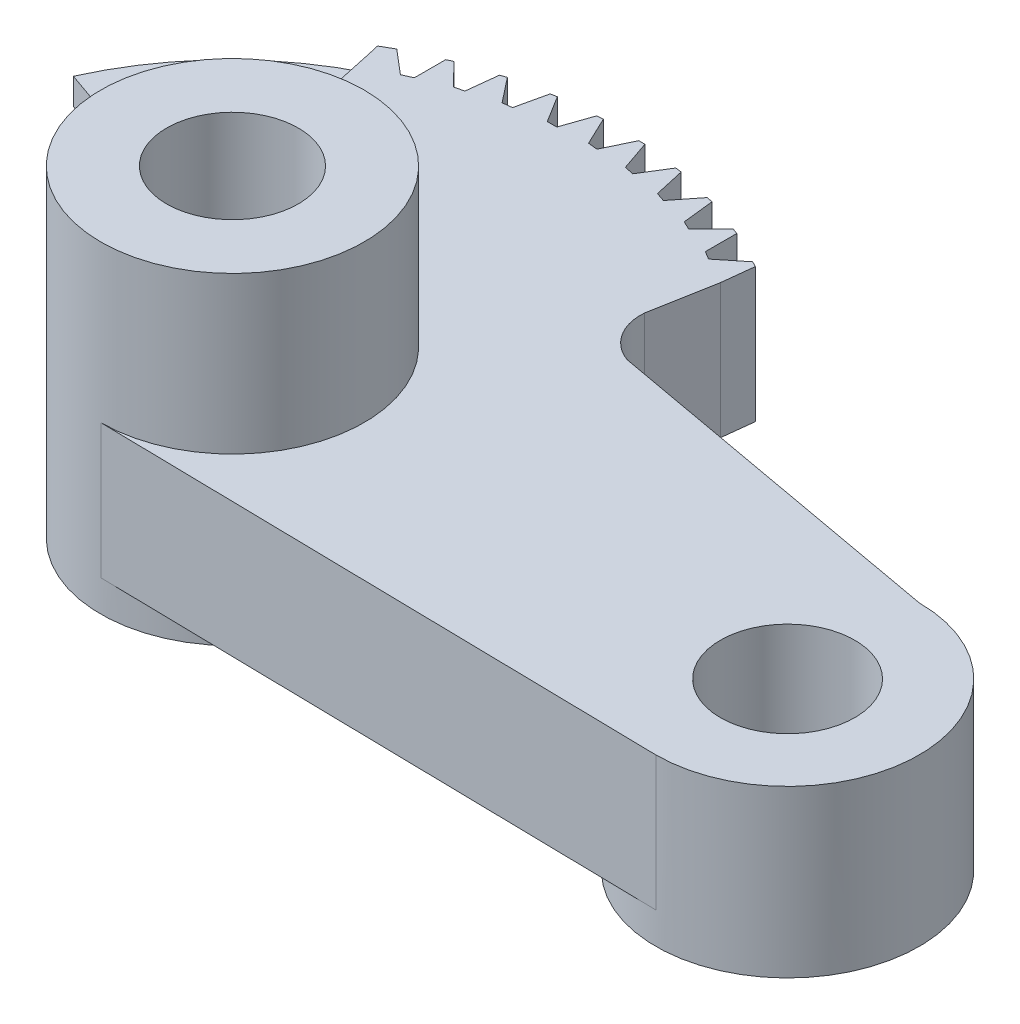
SolidWorks part; units mm, degrees
ref_plane "Спереди" through (0, 0, 0) normal (0, 0, 1) x (1, 0, 0)
ref_plane "Сверху" through (0, 0, 0) normal (0, 1, 0) x (1, 0, 0)
ref_plane "Справа" through (0, 0, 0) normal (1, 0, 0) x (0, 0, -1)
sketch "Эскиз1" plane through (0, 0, 0) normal (0, 1, 0) x (1, 0, 0)
  line L0 (-8.1147, 3.9642) -> (30.3411, -3.1046) construction
  line L1 (-7.0258, 12.1759) -> (-7.131, 12.6394)
  line L2 (0, -5) -> (21.4669, -5.3883)
  line L3 (21.4669, 4.6117) -> (7.9243, 7.0621)
  line L4 (6.718, 8.9283) -> (7.1612, 11.3779)
  line L5 (-2.8983, 13.1359) -> (-3.6342, 14.0716)
  line L6 (-4.339, 12.734) -> (-5.1742, 13.5822)
  line L7 (-3.9893, 12.8157) -> (-3.8571, 13.9987)
  line L9 (-7.131, 12.6394) -> (-6.6667, 12.9059)
  line L10 (-6.6667, 12.9059) -> (-5.7516, 12.1288)
  line L11 (-5.7516, 12.1288) -> (-5.3876, 12.2946)
  line L12 (-3.8571, 13.9987) -> (-3.6342, 14.0716)
  line L13 (-1.422, 13.3754) -> (-2.0494, 14.387)
  line L14 (-2.5417, 13.1782) -> (-2.279, 14.3393)
  line L39 (-2.279, 14.3393) -> (-2.0494, 14.387)
  line L40 (0.0718, 13.4494) -> (-0.4394, 14.5244)
  line L41 (-1.0629, 13.3778) -> (-0.6729, 14.5025)
  line L42 (-0.6729, 14.5025) -> (-0.4394, 14.5244)
  line L43 (1.5646, 13.3571) -> (1.1759, 14.4822)
  line L44 (0.4289, 13.412) -> (0.9414, 14.4864)
  line L45 (0.9414, 14.4864) -> (1.1759, 14.4822)
  line L46 (3.0379, 13.0996) -> (2.7766, 14.261)
  line L47 (1.9154, 13.2803) -> (2.544, 14.2911)
  line L48 (2.544, 14.2911) -> (2.7766, 14.261)
  line L49 (4.4735, 12.6801) -> (4.3427, 13.8633)
  line L50 (3.378, 12.9843) -> (4.1149, 13.9191)
  line L51 (4.1149, 13.9191) -> (4.3427, 13.8633)
  line L52 (5.8536, 12.1038) -> (5.8551, 13.2942)
  line L53 (4.7987, 12.5278) -> (5.6349, 13.375)
  line L54 (5.6349, 13.375) -> (5.8551, 13.2942)
  line L55 (7.1612, 11.3779) -> (7.2948, 12.5607)
  line L56 (6.1599, 11.9163) -> (7.085, 12.6654)
  line L57 (7.085, 12.6654) -> (7.2948, 12.5607)
  line L58 (-4.339, 12.734) -> (-3.9893, 12.8157)
  line L59 (-2.8983, 13.1359) -> (-2.5417, 13.1782)
  line L60 (-1.422, 13.3754) -> (-1.0629, 13.3778)
  line L61 (0.0718, 13.4494) -> (0.4289, 13.412)
  line L62 (1.5646, 13.3571) -> (1.9154, 13.2803)
  line L63 (3.0379, 13.0996) -> (3.378, 12.9843)
  line L64 (4.4735, 12.6801) -> (4.7987, 12.5278)
  line L65 (5.8536, 12.1038) -> (6.1599, 11.9163)
  line L66 (-5.3876, 13.485) -> (-5.3876, 12.2946)
  line L67 (-5.3876, 13.485) -> (-5.1742, 13.5822)
  line L68 (-5.2411, 3.925) -> (-4.7377, 1.5981)
  line L69 (-12.5111, 6.4702) -> (-5.2411, 3.925)
  arc A0 (-4.7377, 1.5981) -> (0, -5) centre (0, 0) ccw
  arc A1 (21.2861, -5.385) -> (21.4669, 4.6117) centre (21.4669, -0.3883) ccw
  arc A2 (7.9243, 7.0621) -> (6.718, 8.9283) centre (8.5382, 8.7819) cw
  arc A3 (-5.4397, 3.9952) -> (-5.4396, 3.9945) centre (1.2447, 4.6512) ccw
  arc A4 (-12.5111, 6.4702) -> (-7.0258, 12.1759) centre (-1.8095, 1.6715) cw
  circle A5 centre (21.4669, -0.3883) radius 2.55
  circle A6 centre (0, 0) radius 2.55
  point P89 (-0.0104, 0.0012)
  dimension "D2" = 1.8261
  dimension "D3" = 9
  dimension "D1" = 39.1
extrude "Бобышка-Вытянуть1" add sketch "Эскиз1" along normal blind 5.1
sketch "Эскиз2" plane through (0, 5.1, 0) normal (0, 1, 0) x (1, 0, 0)
  circle A0 centre (0, 0) radius 5
  circle A1 centre (0, 0) radius 2.5
extrude "Бобышка-Вытянуть2" add sketch "Эскиз2" along normal blind 5.94
sketch "Эскиз4" plane through (0, 0, 0) normal (0, -1, 0) x (1, 0, 0)
  line L0 (-5.2411, -3.925) -> (-7.0258, -12.1759)
  line L1 (-12.5111, -6.4702) -> (-5.2411, -3.925)
  arc A0 (-7.0258, -12.1759) -> (-12.5111, -6.4702) centre (-1.8095, -1.6715) cw
  dimension "D1" = 11.7282
extrude "Вырез-Вытянуть1" cut sketch "Эскиз4" against normal blind 3.5
sketch "Эскиз5" plane through (0, 5.1, 0) normal (0, 1, 0) x (1, 0, 0)
  line L0 (-5.2411, 3.925) -> (-7.0258, 12.1759)
  line L1 (-12.5111, 6.4702) -> (-5.2411, 3.925)
  arc A0 (-7.0258, 12.1759) -> (-12.5111, 6.4702) centre (-1.8095, 1.6715) ccw
  dimension "D1" = 11.7282
extrude "Вырез-Вытянуть3" cut sketch "Эскиз5" against normal blind 0.6
sketch "Эскиз6" plane through (0, 0, 0) normal (0, -1, 0) x (1, 0, 0)
  circle A0 centre (0, 0) radius 5
  circle A1 centre (0, 0) radius 2.5
  circle A2 centre (21.4669, 0.3883) radius 2.5
  circle A3 centre (21.4669, 0.3883) radius 5
extrude "Бобышка-Вытянуть4" add sketch "Эскиз6" along normal blind 1.2
